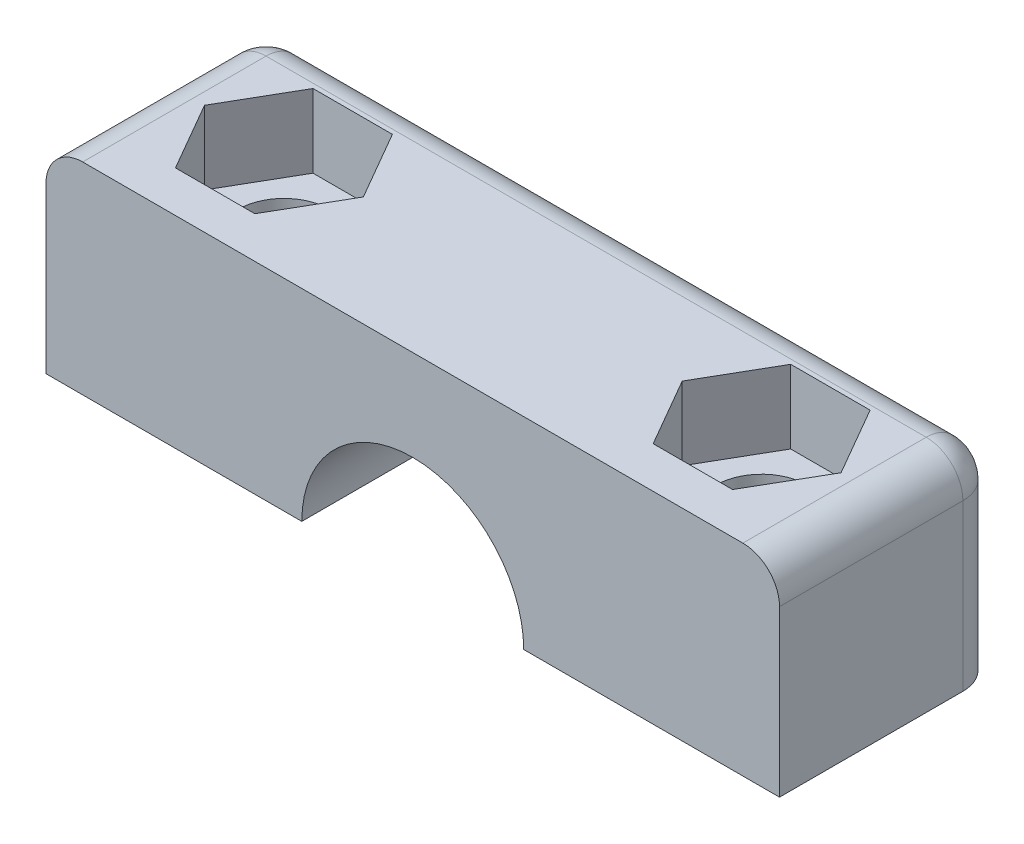
SolidWorks part; units mm, degrees
ref_plane "Plan de face" through (0, 0, 0) normal (0, 0, 1) x (1, 0, 0)
ref_plane "Plan de dessus" through (0, 0, 0) normal (0, 1, 0) x (1, 0, 0)
ref_plane "Plan de droite" through (0, 0, 0) normal (1, 0, 0) x (0, 0, -1)
sketch "Esquisse1" plane through (0, 0, 0) normal (0, 0, 1) x (1, 0, 0)
  line L1 (-16.8144, 9.7258) -> (23.1856, 9.7258)
  line L2 (-16.8144, 9.7258) -> (-16.8144, -8.2742)
  line L3 (-16.8144, -8.2742) -> (23.1856, -8.2742)
  line L4 (23.1856, 9.7258) -> (23.1856, -8.2742)
  dimension "D1" = 40
  dimension "D2" = 18
extrude "Boss.-Extru.1" add sketch "Esquisse1" along normal blind 12
sketch "Esquisse2" plane through (0, -8.2742, 0) normal (0, -1, 0) x (1, 0, 0)
  line L1 (23.1856, 0) -> (-16.8144, 0)
  line L2 (23.1856, 0) -> (23.1856, 12)
  line L3 (23.1856, 12) -> (-16.8144, 12)
  line L4 (-16.8144, 0) -> (-16.8144, 12)
extrude "Boss.-Extru.2" add sketch "Esquisse2" along normal blind 10
sketch "Esquisse3" plane through (0, 0, 12) normal (0, 0, 1) x (1, 0, 0)
  line L0 (3.1856, -18.2742) -> (3.1856, 9.7258) construction
  line L1 (23.1856, -18.2742) -> (-16.8144, -18.2742) construction
  line L2 (23.1856, 9.7258) -> (-16.8144, 9.7258) construction
  line L3 (-2.8644, -18.2742) -> (9.2356, -18.2742)
  arc A0 (-2.8644, -18.2742) -> (9.2356, -18.2742) centre (3.1856, -18.2742) cw
  dimension "D1" = 6.05
extrude "Enlèv. mat.-Extru.1" cut sketch "Esquisse3" against normal up to vertex (12 mm away)
sketch "Esquisse4" plane through (0, -18.2742, 0) normal (0, -1, 0) x (1, 0, 0)
  line L0 (9.2356, 12) -> (23.1856, 0) construction
  line L1 (-2.8644, 0) -> (-16.8144, 12) construction
  circle A0 centre (-9.8394, 6) radius 2.5
  circle A1 centre (16.2106, 6) radius 2.5
  dimension "D1" = 5
  dimension "D2" = 5
extrude "Enlèv. mat.-Extru.2" cut sketch "Esquisse4" against normal up to vertex (28 mm away)
sketch "Esquisse5" plane through (0, 0, 12) normal (0, 0, 1) x (1, 0, 0)
  line L0 (23.1856, 0.7258) -> (-16.8144, 0.7258) construction
  line L1 (23.1856, -18.2742) -> (23.1856, 9.7258) construction
  line L2 (-16.8144, 9.7258) -> (-16.8144, -18.2742) construction
  line L3 (23.1856, 9.7258) -> (-16.8144, 9.7258) construction
  line L4 (9.1856, 0.7258) -> (3.1856, 9.7258) construction
  line L5 (3.1856, 9.7258) -> (-2.8144, 0.7258) construction
  circle A0 centre (9.1856, 0.7258) radius 2.5
  circle A1 centre (-2.8144, 0.7258) radius 2.5
  dimension "D2" = 5
  dimension "D1" = 9
  dimension "D3" = 14
extrude "Enlèv. mat.-Extru.3" cut sketch "Esquisse5" against normal up to vertex (12 mm away)
sketch "Esquisse6" plane through (0, 9.7258, 0) normal (0, 1, 0) x (1, 0, 0)
  circle A0 centre (16.2106, -6) radius 3.5
  circle A1 centre (-9.8394, -6) radius 3.5
  dimension "D1" = 7
sketch "Esquisse7" plane through (0, 0, 0) normal (0, 0, -1) x (-1, 0, 0)
  circle A0 centre (-9.1856, 0.7258) radius 3.5
  circle A1 centre (2.8144, 0.7258) radius 3.5
  dimension "D1" = 7
extrude "Enlèv. mat.-Extru.4" cut sketch "Esquisse7" against normal blind 4
extrude "Enlèv. mat.-Extru.5" cut sketch "Esquisse6" against normal blind 12
fillet "Congé1" radius 2 5 edges at (-16.8144, -4.2742, 0) (23.1856, -4.2742, 0) (23.1856, 9.7258, 6) (-16.8144, 9.7258, 6) (3.1856, 9.7258, 0)
sketch "Esquisse8" plane through (0, 0, 0) normal (0, 0, -1) x (-1, 0, 0)
  line L0 (14.8144, -18.2742) -> (2.8644, -18.2742) construction
  line L1 (-38.6195, 25.3851) -> (25.0007, 25.3851)
  line L2 (-38.6195, 25.3851) -> (-38.6195, -7.2742)
  line L3 (-38.6195, -7.2742) -> (25.0007, -7.2742)
  line L4 (25.0007, 25.3851) -> (25.0007, -7.2742)
  dimension "D1" = 11
extrude "Enlèv. mat.-Extru.6" cut sketch "Esquisse8" against normal up to vertex (12 mm away)
fillet "Congé3" radius 2 5 edges at (23.1856, -7.2742, 7) (22.5998, -7.2742, 0.5858) (-16.8144, -7.2742, 7) (-16.2286, -7.2742, 0.5858) (3.1856, -7.2742, 0)
sketch "Esquisse9" plane through (0, -7.2742, 0) normal (0, 1, 0) x (1, 0, 0)
  line L0 (21.1856, -12) -> (-14.8144, -12) construction
  line L1 (-5.5093, -6) -> (-7.6743, -2.25)
  line L2 (-7.6743, -2.25) -> (-12.0045, -2.25)
  line L3 (-12.0045, -2.25) -> (-14.1695, -6)
  line L4 (-14.1695, -6) -> (-12.0045, -9.75)
  line L5 (-12.0045, -9.75) -> (-7.6743, -9.75)
  line L6 (-7.6743, -9.75) -> (-5.5093, -6)
  line L7 (11.8805, -6) -> (14.0455, -9.75)
  line L8 (14.0455, -9.75) -> (18.3757, -9.75)
  line L9 (18.3757, -9.75) -> (20.5407, -6)
  line L10 (20.5407, -6) -> (18.3757, -2.25)
  line L11 (18.3757, -2.25) -> (14.0455, -2.25)
  line L12 (14.0455, -2.25) -> (11.8805, -6)
  circle A0 centre (-9.8394, -6) radius 3.75 construction
  circle A1 centre (16.2106, -6) radius 3.75 construction
  dimension "D1" = 7.5
extrude "Enlèv. mat.-Extru.7" cut sketch "Esquisse9" against normal blind 4
